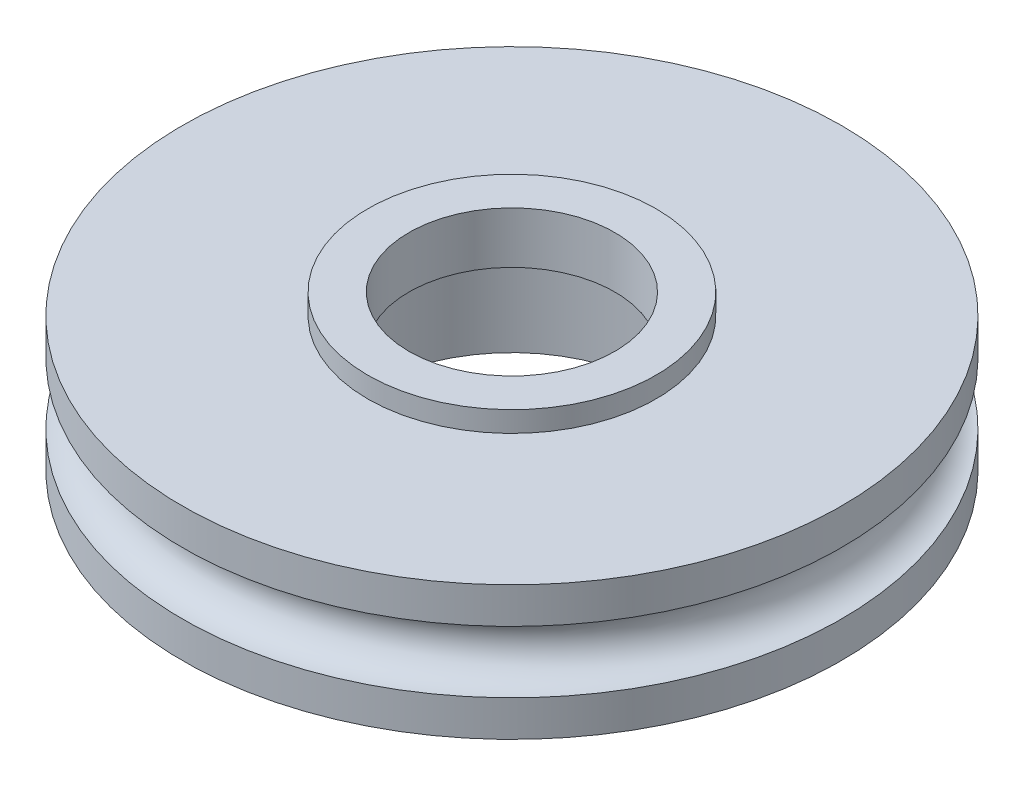
SolidWorks part; units mm, degrees
ref_plane "Front Plane" through (0, 0, 0) normal (0, 0, 1) x (1, 0, 0)
ref_plane "Top Plane" through (0, 0, 0) normal (0, 1, 0) x (1, 0, 0)
ref_plane "Right Plane" through (0, 0, 0) normal (1, 0, 0) x (0, 0, -1)
sketch "Sketch1" plane through (0, 0, 0) normal (0, 1, 0) x (1, 0, 0)
  circle A2 centre (0, 0) radius 3.5
  circle A3 centre (0, 0) radius 8
  dimension "D1" = 7
  dimension "D2" = 16
extrude "Boss-Extrude1" add sketch "Sketch1" along normal mid plane 3.25
sketch "Sketch2" plane through (0, 0, 0) normal (1, 0, 0) x (0, 0, -1)
  line L0 (-8, -1.625) -> (-8, -0.75) construction
  line L1 (-8, 1.625) -> (-8, -1.625) construction
  line L2 (-8, 1.625) -> (-8, 0.75) construction
  line L3 (-8, 0.75) -> (-8, -0.75)
  line L4 (-8, -1.625) -> (8, -1.625) construction
  arc A0 (-8, 0.75) -> (-8, -0.75) centre (-8, 0) cw
  dimension "D1" = 1.5
  dimension "D2" = 0.75
  dimension "D3" = 0.875
revolve "Cut-Revolve1" cut sketch "Sketch2" angle 360 about axis through (0, 1.625, 0) along (0, -1, 0)
sketch "Sketch3" plane through (0, 1.625, 0) normal (0, 1, 0) x (1, 0, 0)
  circle A0 centre (0, 0) radius 3.5
  circle A1 centre (0, 0) radius 2.5
  dimension "D1" = 5
  dimension "D2" = 7
extrude "Boss-Extrude2" add sketch "Sketch3" against normal blind 0.75
sketch "Sketch4" plane through (0, 1.625, 0) normal (0, 1, 0) x (1, 0, 0)
  circle A0 centre (0, 0) radius 2.5
  circle A1 centre (0, 0) radius 3.5
  dimension "D1" = 5
  dimension "D2" = 7
extrude "Boss-Extrude3" add sketch "Sketch4" along normal blind 0.5
